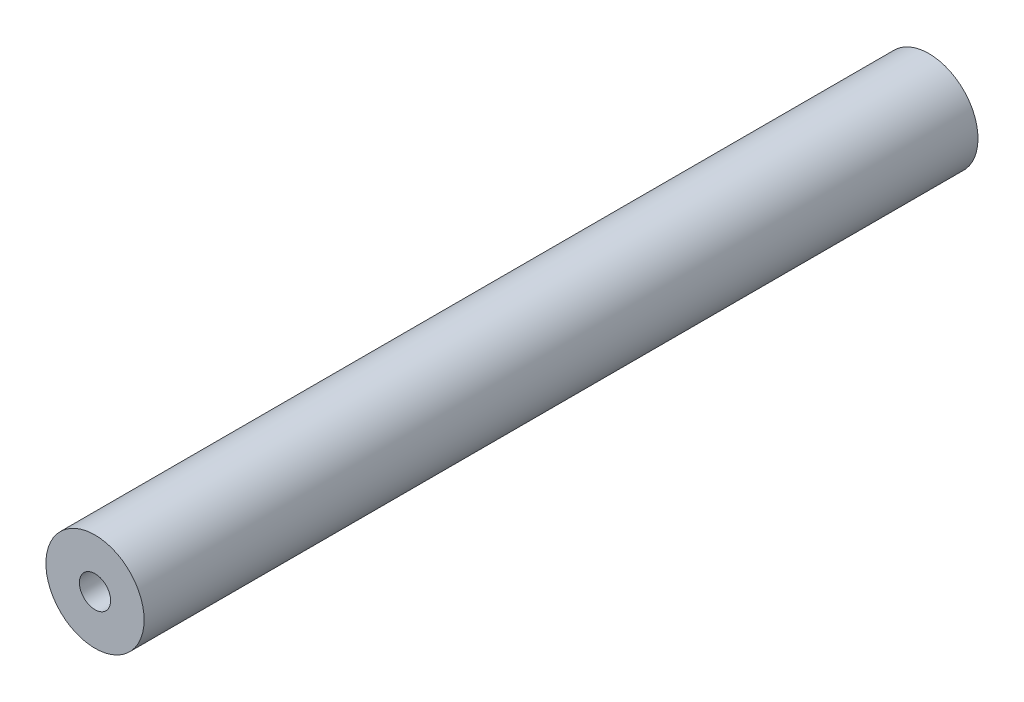
SolidWorks part; units mm, degrees
material "6061-T6 (SS)"
ref_plane "Front Plane" through (0, 0, 0) normal (0, 0, 1) x (1, 0, 0)
ref_plane "Top Plane" through (0, 0, 0) normal (0, 1, 0) x (1, 0, 0)
ref_plane "Right Plane" through (0, 0, 0) normal (1, 0, 0) x (0, 0, -1)
sketch "Sketch1" plane through (0, 0, 0) normal (0, 0, 1) x (1, 0, 0)
  circle A0 centre (0, 0) radius 6.35
  point P4 (0, 0)
  dimension "D1" = 12.7
extrude "Boss-Extrude1" add sketch "Sketch1" along normal blind 107.8484
sketch "Sketch2" plane through (0, 0, 107.8484) normal (0, 0, 1) x (1, 0, 0)
  point P0 (0, 0)
hole_wizard "#10-32 Tapped Hole2" positions "Sketch3" profile "Sketch4" tap size "#10-32" standard "ANSI Inch"
sketch "Sketch3" plane through (0, 0, 107.8484) normal (0, 0, 1) x (1, 0, 0)
  point P0 (0, 0)
sketch "Sketch4" plane through (0, 0, 107.8484) normal (1, 0, 0) x (0, -1, 0)
  line L0 (0, 0) -> (0, 11.1193)
  line L1 (0, 11.1193) -> (2.0193, 9.906)
  line L2 (2.0193, 9.906) -> (2.0193, 0)
  line L5 (2.0193, 0) -> (0, 0)
  line L10 (0, 11.1193) -> (-2.0193, 9.906) construction
  line L11 (0, -6.35) -> (0, 107.95) construction
  dimension "Tap Drill Dia." = 4.0386
  dimension "Tap Drill Depth" = 9.906
  dimension "Drill Angle" = 118
cosmetic thread "Hole Thread1" parameters "D1"=7.62, "D2"=4.826
hole_wizard "#10-32 Tapped Hole1" positions "Sketch7" profile "Sketch8" tap size "#10-32" standard "ANSI Inch"
sketch "Sketch7" plane through (0, 0, 0) normal (0, 0, -1) x (-1, 0, 0)
  point P0 (0, 0)
sketch "Sketch8" plane through (0, 0, 0) normal (1, 0, 0) x (0, 1, 0)
  line L0 (0, 0) -> (0, 13.1513)
  line L1 (0, 13.1513) -> (2.0193, 11.938)
  line L2 (2.0193, 11.938) -> (2.0193, 0)
  line L5 (2.0193, 0) -> (0, 0)
  line L10 (0, 13.1513) -> (-2.0193, 11.938) construction
  line L11 (0, -6.35) -> (0, 107.95) construction
  dimension "Tap Drill Dia." = 4.0386
  dimension "Tap Drill Depth" = 11.938
  dimension "Drill Angle" = 118
cosmetic thread "Hole Thread2" parameters "D1"=9.652, "D2"=4.826
